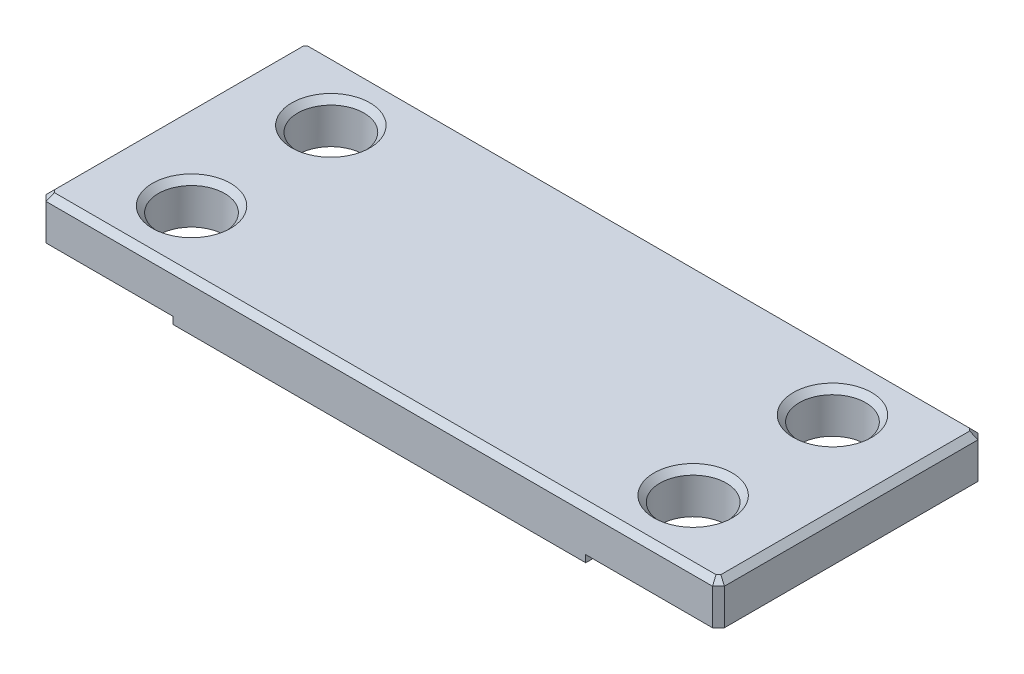
SolidWorks part; units mm, degrees
ref_plane "Front Plane" through (0, 0, 0) normal (0, 0, 1) x (1, 0, 0)
ref_plane "Top Plane" through (0, 0, 0) normal (0, 1, 0) x (1, 0, 0)
ref_plane "Right Plane" through (0, 0, 0) normal (1, 0, 0) x (0, 0, -1)
sketch "Sketch1" plane through (0, 0, 0) normal (0, 1, 0) x (1, 0, 0)
  line L1 (-36.5125, 14.2875) -> (36.5125, 14.2875)
  line L2 (-36.5125, 14.2875) -> (-36.5125, -14.2875)
  line L3 (-36.5125, -14.2875) -> (36.5125, -14.2875)
  line L4 (36.5125, 14.2875) -> (36.5125, -14.2875)
  line L5 (-36.5125, 14.2875) -> (36.5125, -14.2875) construction
  line L6 (-36.5125, -14.2875) -> (36.5125, 14.2875) construction
  point P0 (0, 0)
  dimension "D1" = 28.575
  dimension "D2" = 73.025
extrude "Boss-Extrude1" add sketch "Sketch1" along normal blind 5.274
sketch "Sketch2" plane through (0, 0, 14.2875) normal (0, 0, 1) x (1, 0, 0)
  line L1 (-36.5125, 0) -> (-22.225, 0)
  line L2 (-36.5125, 0) -> (-36.5125, 0.762)
  line L3 (-36.5125, 0.762) -> (-22.225, 0.762)
  line L4 (-22.225, 0) -> (-22.225, 0.762)
  line L5 (36.5125, 0) -> (22.225, 0)
  line L6 (36.5125, 0) -> (36.5125, 0.762)
  line L7 (36.5125, 0.762) -> (22.225, 0.762)
  line L8 (22.225, 0) -> (22.225, 0.762)
  dimension "D1" = 0.762
  dimension "D2" = 44.45
extrude "Cut-Extrude1" cut sketch "Sketch2" against normal through all
hole_wizard "9/32 (0.28125) Diameter Hole1" positions "Sketch4" profile "Sketch3" hole size "9/32" standard "ANSI Inch" end condition through all
sketch "Sketch4" plane through (0, 5.274, 0) normal (0, 1, 0) x (-1, 0, 0)
  line L2 (-27, 7.5) -> (27, 7.5)
  line L3 (-27, 7.5) -> (-27, -7.5)
  line L4 (-27, -7.5) -> (27, -7.5)
  line L5 (27, 7.5) -> (27, -7.5)
  line L6 (-27, 7.5) -> (27, -7.5) construction
  line L7 (-27, -7.5) -> (27, 7.5) construction
  point P122 (27, -7.5)
  point P161 (-27, 7.5)
  point P162 (-27, -7.5)
  point P163 (27, 7.5)
  point P176 (0, 0)
  dimension "D1" = 54
  dimension "D2" = 15
sketch "Sketch3" plane through (-27, 5.274, -7.5) normal (1, 0, 0) x (0, 0, 1)
  line L0 (0, 0) -> (0, 5.274)
  line L1 (0, 5.274) -> (3.5719, 5.274)
  line L2 (3.5719, 5.274) -> (3.5719, 0)
  line L5 (3.5719, 0) -> (0, 0)
  line L11 (0, -6.35) -> (0, 107.95) construction
  dimension "Thru Hole Dia." = 7.1437
  dimension "Thru Hole Depth" = 5.274
chamfer "Chamfer1" distance 0.635 angle 45 4 edges at (36.5125, 3.018, 14.2875) (36.5125, 3.018, -14.2875) (-36.5125, 3.018, -14.2875) (-36.5125, 3.018, 14.2875)
chamfer "Chamfer2" distance 0.635 angle 45 12 edges at (-36.195, 5.274, 13.97) (-36.5125, 5.274, 0) (-36.195, 5.274, -13.97) (0, 5.274, -14.2875) (36.195, 5.274, -13.97) (36.5125, 5.274, 0) (36.195, 5.274, 13.97) (0, 5.274, 14.2875) (-27, 5.274, 11.0719) (27, 5.274, -3.9281) (27, 5.274, 11.0719) (-27, 5.274, -3.9281)
